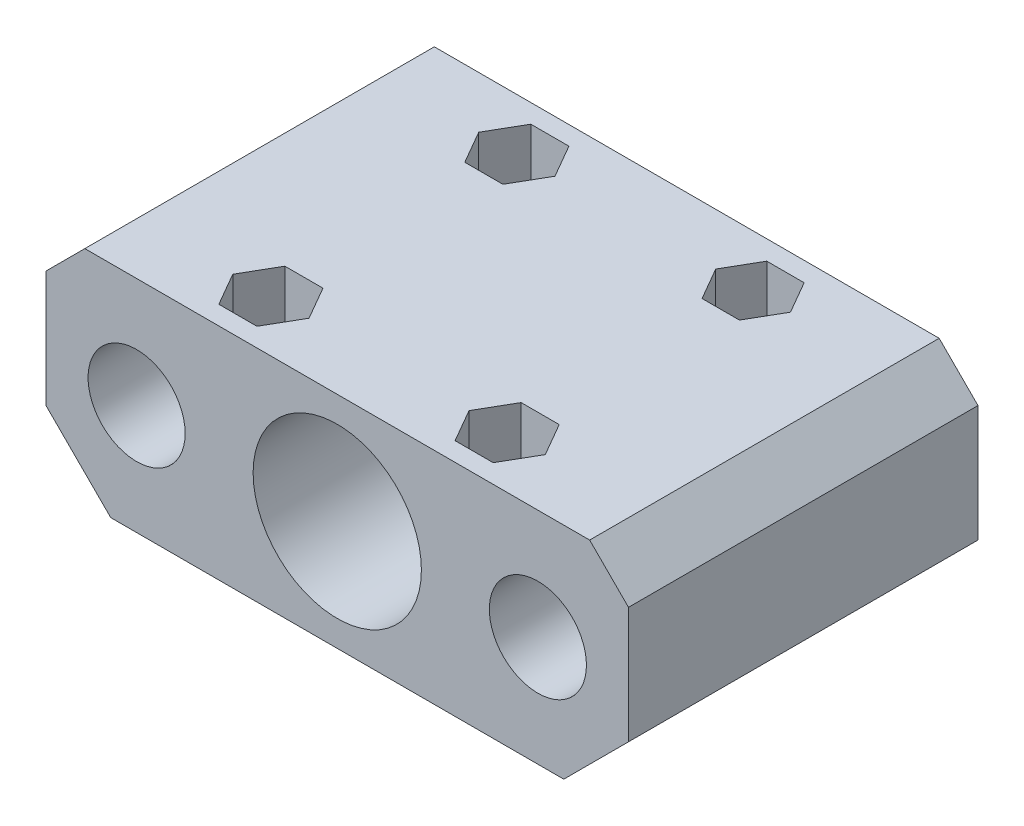
SolidWorks part; units mm, degrees
ref_plane "Front Plane" through (0, 0, 0) normal (0, 0, 1) x (1, 0, 0)
ref_plane "Top Plane" through (0, 0, 0) normal (0, 1, 0) x (1, 0, 0)
ref_plane "Right Plane" through (0, 0, 0) normal (1, 0, 0) x (0, 0, -1)
sketch "Sketch1" plane through (0, 0, 0) normal (0, 0, 1) x (1, 0, 0)
  line L0 (90, 17) -> (0, 17) construction
  line L1 (0, 0) -> (90, 0)
  line L2 (0, 0) -> (0, 34)
  line L3 (0, 34) -> (90, 34)
  line L4 (90, 0) -> (90, 34)
  circle A0 centre (45, 17) radius 7
  circle A1 centre (14, 17) radius 7.5
  circle A2 centre (76, 17) radius 7.5
  dimension "D3" = 15
  dimension "16" = 14
  dimension "D1" = 34
  dimension "D2" = 90
  dimension "D4" = 14
  dimension "D5" = 14
extrude "Boss-Extrude1" add sketch "Sketch1" along normal blind 54
chamfer "Chamfer1" distance 6 angle 45 2 edges at (0, 34, 27) (90, 34, 27)
chamfer "Chamfer2" distance 10 angle 45 2 edges at (0, 0, 27) (90, 0, 27)
sketch "Sketch2" plane through (0, 0, 54) normal (0, 0, 1) x (1, 0, 0)
  circle A0 centre (45, 17) radius 13
  dimension "D1" = 26
extrude "Cut-Extrude1" cut sketch "Sketch2" against normal blind 32
sketch "Sketch3" plane through (0, 34, 0) normal (0, 1, 0) x (1, 0, 0)
  line L0 (84, 0) -> (6, 0) construction
  line L1 (0, -54) -> (0, 0) construction
  line L2 (84, -54) -> (6, -54) construction
  line L3 (90, 0) -> (90, -54) construction
  circle A0 centre (26.75, -8) radius 3.1
  circle A1 centre (63.25, -8) radius 3.1
  circle A2 centre (63.25, -46) radius 3.1
  circle A3 centre (26.75, -46) radius 3.1
  dimension "D2" = 6.2
  dimension "D1" = 8
  dimension "D3" = 26.75
  dimension "8" = 8
  dimension "26.75" = 26.75
extrude "Cut-Extrude2" cut sketch "Sketch3" against normal through all
sketch "Sketch4" plane through (0, 34, 0) normal (0, 1, 0) x (1, 0, 0)
  line L1 (23.8055, -13.1) -> (29.6945, -13.1)
  line L2 (29.6945, -13.1) -> (32.639, -8)
  line L3 (32.639, -8) -> (29.6945, -2.9)
  line L4 (29.6945, -2.9) -> (23.8055, -2.9)
  line L5 (23.8055, -2.9) -> (20.861, -8)
  line L6 (20.861, -8) -> (23.8055, -13.1)
  line L7 (60.3632, -13) -> (66.1368, -13)
  line L8 (66.1368, -13) -> (69.0235, -8)
  line L9 (69.0235, -8) -> (66.1368, -3)
  line L10 (66.1368, -3) -> (60.3632, -3)
  line L11 (60.3632, -3) -> (57.4765, -8)
  line L12 (57.4765, -8) -> (60.3632, -13)
  line L13 (60.3055, -51.1) -> (66.1945, -51.1)
  line L14 (66.1945, -51.1) -> (69.139, -46)
  line L15 (69.139, -46) -> (66.1945, -40.9)
  line L16 (66.1945, -40.9) -> (60.3055, -40.9)
  line L17 (60.3055, -40.9) -> (57.361, -46)
  line L18 (57.361, -46) -> (60.3055, -51.1)
  line L25 (29.6945, -51.1) -> (32.639, -46)
  line L26 (32.639, -46) -> (29.6945, -40.9)
  line L27 (29.6945, -40.9) -> (23.8055, -40.9)
  line L28 (23.8055, -40.9) -> (20.861, -46)
  line L29 (20.861, -46) -> (23.8055, -51.1)
  line L30 (23.8055, -51.1) -> (29.6945, -51.1)
  circle A0 centre (26.75, -8) radius 5.1 construction
  circle A1 centre (63.25, -8) radius 5 construction
  circle A2 centre (63.25, -46) radius 5.1 construction
  circle A3 centre (26.75, -46) radius 5.1 construction
  dimension "D1" = 10.2
  dimension "10" = 10
extrude "Cut-Extrude3" cut sketch "Sketch4" against normal blind 10
sketch "Sketch5" plane through (0, 0, 22) normal (0, 0, 1) x (1, 0, 0)
  line L0 (45, 17) -> (45, 25) construction
  circle A0 centre (45, 25) radius 1.5
  dimension "D1" = 3
  dimension "8" = 8
extrude "Cut-Extrude4" cut sketch "Sketch5" against normal through all
pattern_circular "CirPattern1" count 4 every 90 about axis through (45, 17, 0) along (0, 0, 1) of "Cut-Extrude4"
chamfer "Chamfer3" distance 0.5 angle 45 4 edges at (26.75, 0, 11.1) (26.75, 0, 49.1) (63.25, 0, 11.1) (63.25, 0, 49.1)
